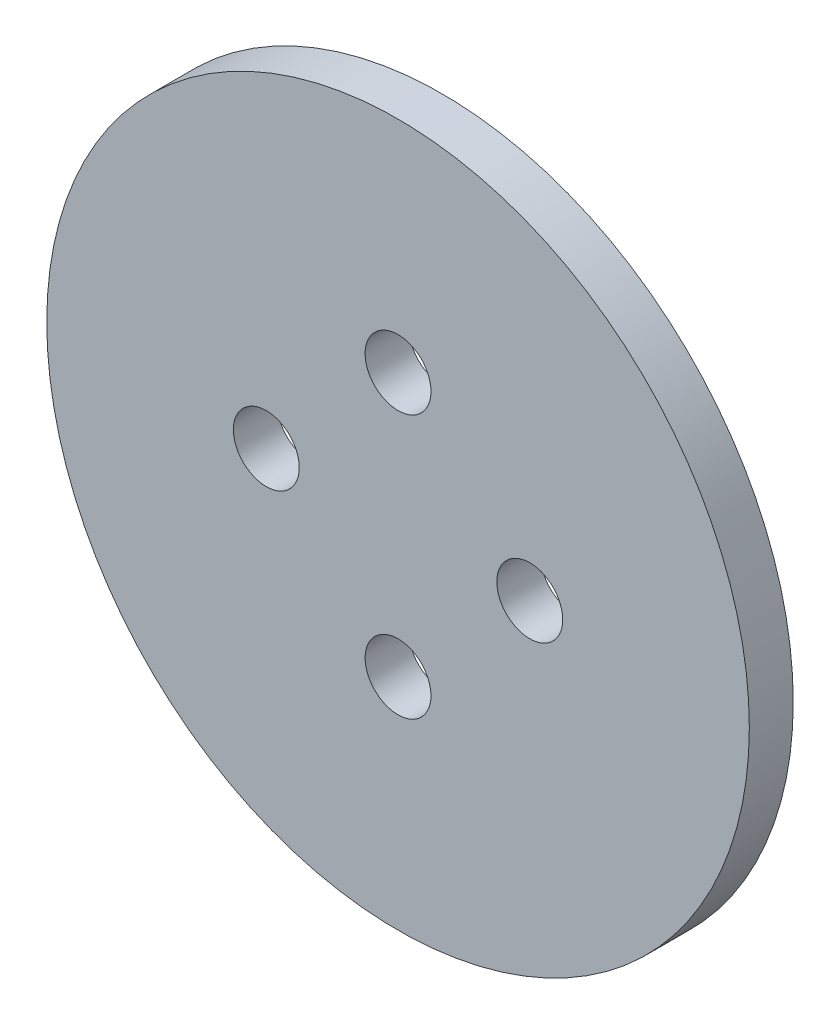
SolidWorks part; units mm, degrees
ref_plane "Front Plane" through (0, 0, 0) normal (0, 0, 1) x (1, 0, 0)
ref_plane "Top Plane" through (0, 0, 0) normal (0, 1, 0) x (1, 0, 0)
ref_plane "Right Plane" through (0, 0, 0) normal (1, 0, 0) x (0, 0, -1)
sketch "Sketch1" plane through (0, 0, 0) normal (0, 0, 1) x (1, 0, 0)
  circle A0 centre (0, 0) radius 25.4
  circle A1 centre (0, 9.525) radius 2.3813
  circle A2 centre (9.525, 0) radius 2.3812
  circle A3 centre (0, -9.525) radius 2.3813
  circle A4 centre (-9.525, 0) radius 2.3813
  point P14 (0, 0)
  dimension "D1" = 50.8
  dimension "D2" = 9.525
  dimension "D3" = 4.7625
  dimension "D4" = 4
extrude "Boss-Extrude1" add sketch "Sketch1" along normal blind 3.175
